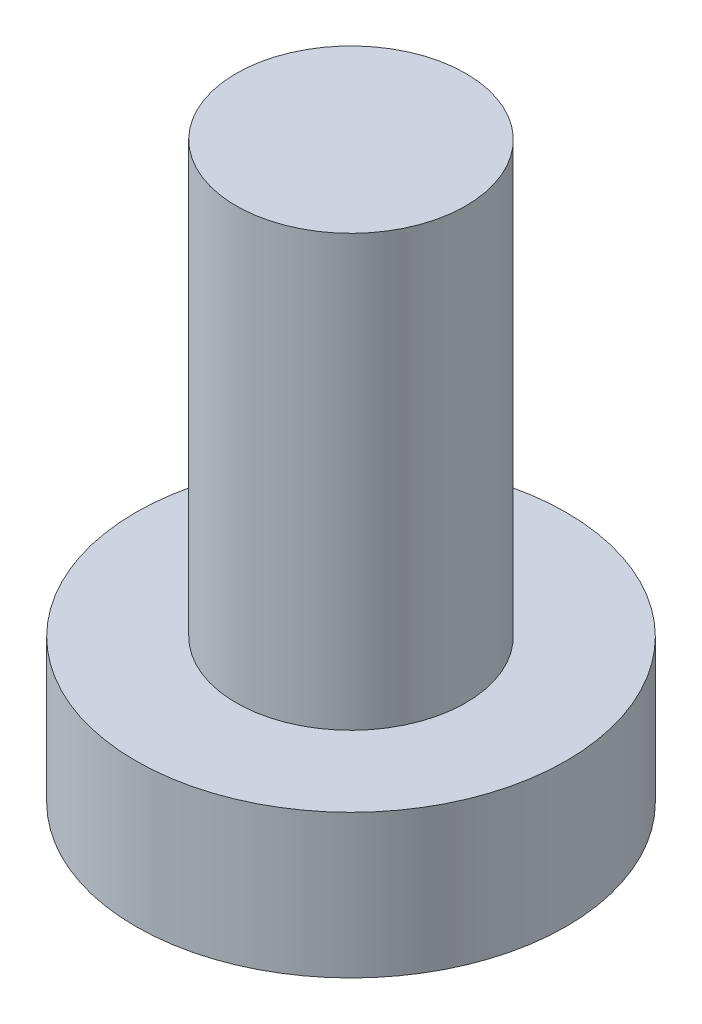
SolidWorks part; units mm, degrees
ref_plane "Ön Düzlem" through (0, 0, 0) normal (0, 0, 1) x (1, 0, 0)
ref_plane "Üst Düzlem" through (0, 0, 0) normal (0, 1, 0) x (1, 0, 0)
ref_plane "Sağ Düzlem" through (0, 0, 0) normal (1, 0, 0) x (0, 0, -1)
sketch "Sketch1" plane through (0, 0, 0) normal (0, 0, 1) x (1, 0, 0)
  line L0 (0, 0) -> (0, 20)
  line L1 (0, 20) -> (4, 20)
  line L2 (4, 20) -> (4, 5)
  line L3 (4, 5) -> (7.5, 5)
  line L4 (7.5, 5) -> (7.5, 0)
  line L5 (7.5, 0) -> (0, 0)
  dimension "D1" = 5
  dimension "D2" = 7.5
  dimension "D3" = 4
  dimension "D4" = 15
revolve "Revolve1" add sketch "Sketch1" angle 360 about L0
